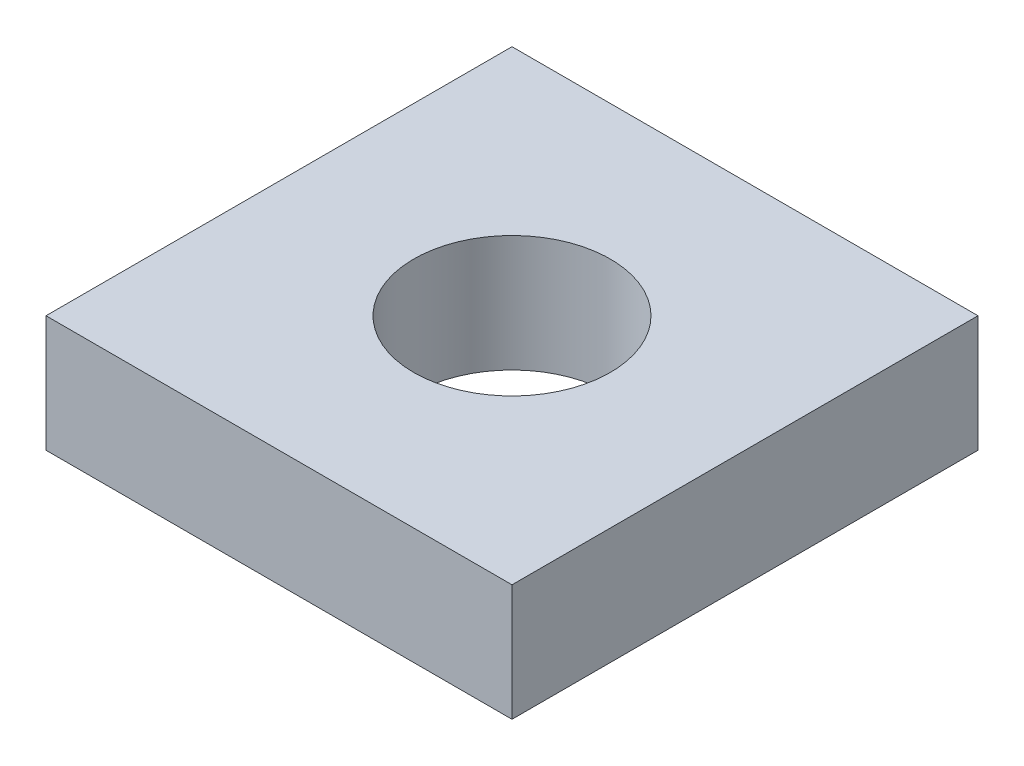
SolidWorks part; units mm, degrees
other "DetailItem1"
ref_plane "Front Plane" through (0, 0, 0) normal (0, 0, 1) x (1, 0, 0)
ref_plane "Top Plane" through (0, 0, 0) normal (0, 1, 0) x (1, 0, 0)
ref_plane "Right Plane" through (0, 0, 0) normal (1, 0, 0) x (0, 0, -1)
sketch "Sketch1" plane through (0, 0, 0) normal (0, 1, 0) x (1, 0, 0)
  line L1 (-12.7, -12.7) -> (12.7, -12.7)
  line L2 (-12.7, -12.7) -> (-12.7, 12.7)
  line L3 (-12.7, 12.7) -> (12.7, 12.7)
  line L4 (12.7, -12.7) -> (12.7, 12.7)
  line L5 (-12.7, -12.7) -> (12.7, 12.7) construction
  line L6 (-12.7, 12.7) -> (12.7, -12.7) construction
  circle A0 centre (0, 0) radius 5.3578
  point P0 (0, 0)
  dimension "D2" = 10.7156
  dimension "D1" = 25.4
extrude "Boss-Extrude1" add sketch "Sketch1" along normal blind 6.35
